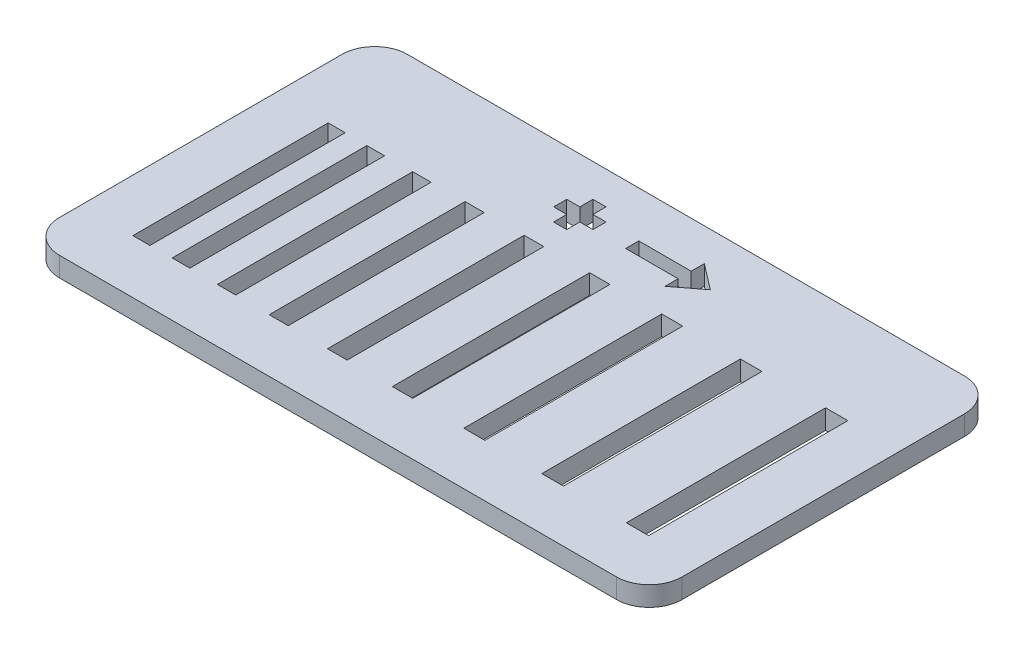
SolidWorks part; units mm, degrees
ref_plane "Front Plane" through (0, 0, 0) normal (0, 0, 1) x (1, 0, 0)
ref_plane "Top Plane" through (0, 0, 0) normal (0, 1, 0) x (1, 0, 0)
ref_plane "Right Plane" through (0, 0, 0) normal (1, 0, 0) x (0, 0, -1)
sketch "Sketch1" plane through (0, 0, 0) normal (0, 1, 0) x (1, 0, 0)
  line L0 (1, 21) -> (3, 21)
  line L5 (0, 30) -> (0, -23.1) construction
  line L6 (-39.3, 0) -> (55.7, 0) construction
  line L11 (-25.35, -14.85) -> (-22.65, -14.85)
  line L12 (-25.35, -14.85) -> (-25.35, 14.85)
  line L13 (-18.4, -14.9) -> (-15.6, -14.9)
  line L14 (-18.4, -14.9) -> (-18.4, 14.9)
  line L15 (-18.4, 14.9) -> (-15.6, 14.9)
  line L16 (-15.6, -14.9) -> (-15.6, 14.9)
  line L17 (-18.4, -14.9) -> (-15.6, 14.9) construction
  line L18 (-18.4, 14.9) -> (-15.6, -14.9) construction
  line L19 (-10.45, -14.95) -> (-7.55, -14.95)
  line L20 (-10.45, -14.95) -> (-10.45, 14.95)
  line L21 (-10.45, 14.95) -> (-7.55, 14.95)
  line L22 (-7.55, -14.95) -> (-7.55, 14.95)
  line L23 (-10.45, -14.95) -> (-7.55, 14.95) construction
  line L24 (-10.45, 14.95) -> (-7.55, -14.95) construction
  line L25 (-1.5, -15) -> (1.5, -15)
  line L26 (-1.5, -15) -> (-1.5, 15)
  line L27 (-1.5, 15) -> (1.5, 15)
  line L28 (1.5, -15) -> (1.5, 15)
  line L29 (-1.5, -15) -> (1.5, 15) construction
  line L30 (-1.5, 15) -> (1.5, -15) construction
  line L31 (8.45, -15.05) -> (11.55, -15.05)
  line L32 (8.45, -15.05) -> (8.45, 15.05)
  line L33 (8.45, 15.05) -> (11.55, 15.05)
  line L34 (11.55, -15.05) -> (11.55, 15.05)
  line L35 (8.45, -15.05) -> (11.55, 15.05) construction
  line L36 (8.45, 15.05) -> (11.55, -15.05) construction
  line L37 (19.4, -15.1) -> (22.6, -15.1)
  line L38 (19.4, -15.1) -> (19.4, 15.1)
  line L39 (19.4, 15.1) -> (22.6, 15.1)
  line L40 (22.6, -15.1) -> (22.6, 15.1)
  line L41 (19.4, -15.1) -> (22.6, 15.1) construction
  line L42 (19.4, 15.1) -> (22.6, -15.1) construction
  line L47 (-25.35, 14.85) -> (-22.65, 14.85)
  line L48 (-22.65, -14.85) -> (-22.65, 14.85)
  line L49 (-25.35, -14.85) -> (-22.65, 14.85) construction
  line L50 (-25.35, 14.85) -> (-22.65, -14.85) construction
  line L51 (31.35, -15.15) -> (34.65, -15.15)
  line L52 (31.35, -15.15) -> (31.35, 15.15)
  line L53 (31.35, 15.15) -> (34.65, 15.15)
  line L54 (34.65, -15.15) -> (34.65, 15.15)
  line L55 (31.35, -15.15) -> (34.65, 15.15) construction
  line L56 (31.35, 15.15) -> (34.65, -15.15) construction
  line L57 (-28.7, -14.9) -> (-31.3, -14.9)
  line L58 (-28.7, -14.9) -> (-28.7, 14.9)
  line L59 (-28.7, 14.9) -> (-31.3, 14.9)
  line L60 (-31.3, -14.9) -> (-31.3, 14.9)
  line L61 (-28.7, -14.9) -> (-31.3, 14.9) construction
  line L62 (-28.7, 14.9) -> (-31.3, -14.9) construction
  line L63 (44.3, -15.2) -> (47.7, -15.2)
  line L64 (44.3, -15.2) -> (44.3, 15.2)
  line L65 (44.3, 15.2) -> (47.7, 15.2)
  line L66 (47.7, -15.2) -> (47.7, 15.2)
  line L67 (44.3, -15.2) -> (47.7, 15.2) construction
  line L68 (44.3, 15.2) -> (47.7, -15.2) construction
  line L69 (50.7, -23.1) -> (-34.3, -23.1)
  line L70 (55.7, -18.1) -> (55.7, 25)
  line L71 (50.7, 30) -> (-34.3, 30)
  line L72 (-39.3, -18.1) -> (-39.3, 25)
  line L73 (1, 25) -> (-1, 25)
  line L74 (1, 25) -> (1, 23)
  line L75 (1, 19) -> (-1, 19)
  line L76 (-1, 25) -> (-1, 23)
  line L77 (0, 19) -> (0, 25) construction
  line L78 (16, 23) -> (16, 25)
  line L79 (-3, 23) -> (-1, 23)
  line L80 (-3, 23) -> (-3, 21)
  line L81 (-3, 21) -> (-1, 21)
  line L82 (3, 23) -> (3, 21)
  line L83 (16, 25) -> (19.9097, 22)
  line L84 (-3, 22) -> (3, 22) construction
  line L85 (-1, 21) -> (-1, 19)
  line L86 (1, 23) -> (3, 23)
  line L87 (1, 21) -> (1, 19)
  line L88 (19.9097, 22) -> (16, 19)
  line L89 (8, 23) -> (16, 23)
  line L90 (8, 23) -> (8, 21)
  line L91 (8, 21) -> (16, 21)
  line L93 (12, 21) -> (12, 23) construction
  line L94 (8, 22) -> (19.9097, 22) construction
  line L95 (16, 19) -> (16, 21)
  arc A0 (55.7, -18.1) -> (50.7, -23.1) centre (50.7, -18.1) cw
  arc A1 (-34.3, -23.1) -> (-39.3, -18.1) centre (-34.3, -18.1) cw
  arc A2 (55.7, 25) -> (50.7, 30) centre (50.7, 25) ccw
  arc A3 (-39.3, 25) -> (-34.3, 30) centre (-34.3, 25) cw
  point P4 (-9, 0)
  point P5 (-24, 0)
  point P12 (-17, 0)
  point P21 (0, 0)
  point P26 (10, 0)
  point P31 (21, 0)
  point P36 (33, 0)
  point P41 (-30, 0)
  point P46 (46, 0)
  point P65 (0, 0)
  point P68 (0, 0)
  point P76 (0, 0)
  point P77 (0, 0)
  point P78 (0, 0)
  point P93 (0, 22)
  point P96 (55.7, -23.1)
  point P99 (-39.3, -23.1)
  point P102 (55.7, 30)
  point P133 (0, 22)
  point P142 (12, 22)
  dimension "D38" = 5
  dimension "D1" = 3
  dimension "D2" = 2.9
  dimension "D3" = 2.8
  dimension "D4" = 2.7
  dimension "D5" = 3.1
  dimension "D6" = 3.2
  dimension "D7" = 3.3
  dimension "D8" = 2.6
  dimension "D9" = 3.4
  dimension "D10" = 30
  dimension "D11" = 30.1
  dimension "D12" = 30.2
  dimension "D13" = 30.3
  dimension "D14" = 30.4
  dimension "D15" = 29.9
  dimension "D16" = 29.8
  dimension "D17" = 29.7
  dimension "D18" = 29.8
  dimension "D19" = 10
  dimension "D20" = 11
  dimension "D21" = 12
  dimension "D22" = 13
  dimension "D23" = 9
  dimension "D24" = 8
  dimension "D25" = 7
  dimension "D26" = 6
  dimension "D27" = 8
  dimension "D28" = 8
  dimension "D29" = 2
  dimension "D30" = 2
  dimension "D31" = 6
  dimension "D32" = 6
  dimension "D33" = 8
  dimension "D34" = 75
  dimension "D35" = 4
  dimension "D36" = 5
  dimension "D37" = 8
  dimension "D39" = 5
extrude "Boss-Extrude1" add sketch "Sketch1" along normal blind 3
